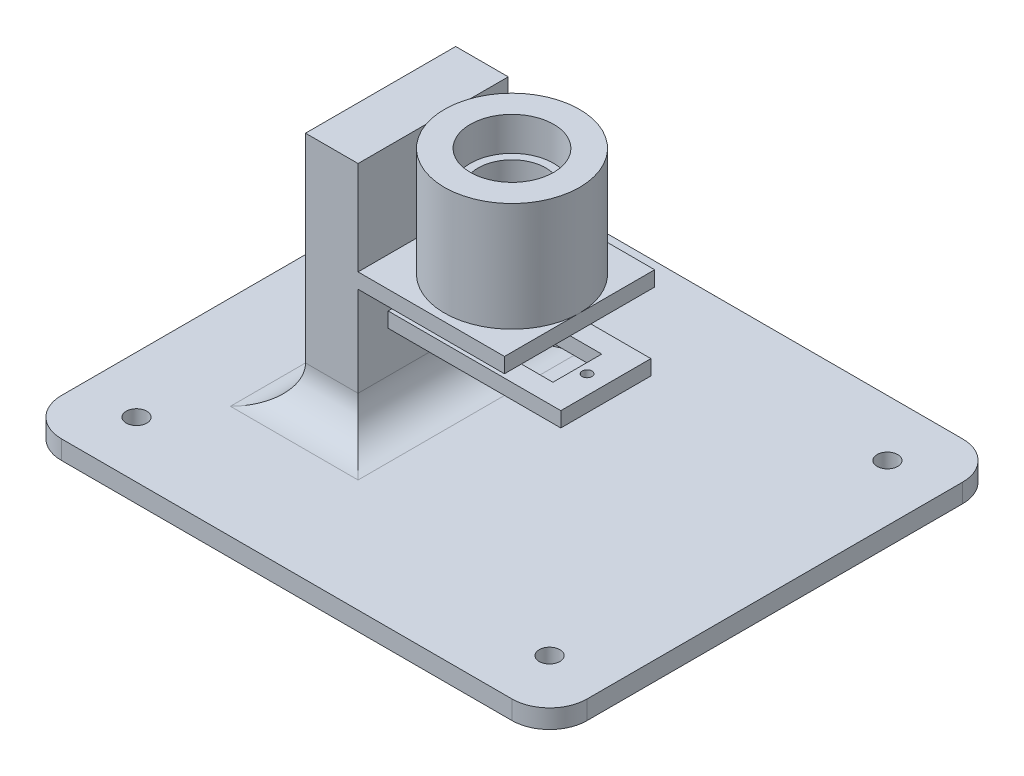
SolidWorks part; units mm, degrees
ref_plane "Front Plane" through (0, 0, 0) normal (0, 0, 1) x (1, 0, 0)
ref_plane "Top Plane" through (0, 0, 0) normal (0, 1, 0) x (1, 0, 0)
ref_plane "Right Plane" through (0, 0, 0) normal (1, 0, 0) x (0, 0, -1)
sketch "Bench_footprint_140x120_profile" plane through (0, 0, 0) normal (0, 1, 0) x (1, 0, 0)
  line L1 (-60, -60) -> (60, -60)
  line L2 (-70, -50) -> (-70, 50)
  line L3 (-60, 60) -> (60, 60)
  line L4 (70, -50) -> (70, 50)
  arc A1 (-60, -60) -> (-70, -50) centre (-60, -50) cw
  arc A2 (60, -60) -> (70, -50) centre (60, -50) ccw
  arc A3 (60, 60) -> (70, 50) centre (60, 50) cw
  arc A4 (-70, 50) -> (-60, 60) centre (-60, 50) cw
  point P4 (-70, -60)
  point P10 (70, -60)
  point P15 (-70, 60)
  dimension "D5" = 10
  dimension "D1" = 140
  dimension "D2" = 120
  dimension "D3" = 60
  dimension "D4" = 70
extrude "Bench_footprint_140x120" add sketch "Bench_footprint_140x120_profile" along normal blind 5
sketch "Backbone_profile" plane through (0, 0, 0) normal (0, 0, 1) x (1, 0, 0)
  line L0 (-60, 5) -> (60, 5) construction
  line L1 (-35, 5) -> (-21, 5)
  line L2 (-35, 5) -> (-35, 68)
  line L3 (-35, 68) -> (-21, 68)
  line L4 (-21, 5) -> (-21, 68)
  dimension "D1" = 14
  dimension "D2" = 63
  dimension "D3" = 35
  dimension "D4" = 0
extrude "Backbone" add sketch "Backbone_profile" along normal blind 40 from offset 20
sketch "Servo_shelf_profile" plane through (0, 0, 0) normal (0, 1, 0) x (1, 0, 0)
  line L1 (-35, -12) -> (25, -12)
  line L2 (-35, -12) -> (-35, 12)
  line L3 (-35, 12) -> (25, 12)
  line L4 (25, -12) -> (25, 12)
  dimension "D1" = 60
  dimension "D2" = 24
extrude "Servo_shelf" add sketch "Servo_shelf_profile" along normal blind 4 from offset 26
sketch "Servo_body_window_profile" plane through (0, 0, 0) normal (0, 1, 0) x (1, 0, 0)
  line L1 (-6.4, -6.5) -> (17.4, -6.5)
  line L2 (-6.4, -6.5) -> (-6.4, 6.5)
  line L3 (-6.4, 6.5) -> (17.4, 6.5)
  line L4 (17.4, -6.5) -> (17.4, 6.5)
  dimension "D1" = 23.8
  dimension "D2" = 13
extrude "Servo_body_window" cut sketch "Servo_body_window_profile" along normal through all from offset 25
sketch "Yaw_servo_fasteners_profile" plane through (0, 0, 0) normal (0, 1, 0) x (1, 0, 0)
  circle A0 centre (-9, 0) radius 1.3
  circle A1 centre (20, 0) radius 1.3
  dimension "D1" = 2.6
  dimension "D2" = 2.6
extrude "Yaw_servo_fasteners" cut sketch "Yaw_servo_fasteners_profile" along normal through all from offset 25
sketch "Bearing_bridge_profile" plane through (0, 0, 0) normal (0, 1, 0) x (1, 0, 0)
  line L1 (-35, -20) -> (18, -20)
  line L2 (-35, -20) -> (-35, 20)
  line L3 (-35, 20) -> (18, 20)
  line L4 (18, -20) -> (18, 20)
  dimension "D1" = 53
  dimension "D2" = 40
extrude "Bearing_bridge" add sketch "Bearing_bridge_profile" along normal blind 4 from offset 39
sketch "Bridge_horn_clearance_profile" plane through (0, 0, 0) normal (0, 1, 0) x (1, 0, 0)
  circle A0 centre (0, 0) radius 14
  dimension "D1" = 28
extrude "Bridge_horn_clearance" cut sketch "Bridge_horn_clearance_profile" along normal through all from offset 38
sketch "Drive_collar_chamber_profile" plane through (0, 0, 0) normal (0, 1, 0) x (1, 0, 0)
  circle A0 centre (0, 0) radius 18
  circle A1 centre (0, 0) radius 14
  dimension "D1" = 36
  dimension "D2" = 28
extrude "Drive_collar_chamber" add sketch "Drive_collar_chamber_profile" along normal blind 5 from offset 43
sketch "Bearing_tower_profile" plane through (0, 0, 0) normal (0, 1, 0) x (1, 0, 0)
  circle A0 centre (0, 0) radius 18
  circle A1 centre (0, 0) radius 11.1
  dimension "D1" = 36
  dimension "D2" = 22.2
extrude "Bearing_tower" add sketch "Bearing_tower_profile" along normal blind 24 from offset 48
sketch "Bearing_separation_shoulder_profile" plane through (0, 0, 0) normal (0, 1, 0) x (1, 0, 0)
  circle A0 centre (0, 0) radius 11.1
  circle A1 centre (0, 0) radius 9
  dimension "D1" = 22.2
  dimension "D2" = 18
extrude "Bearing_separation_shoulder" add sketch "Bearing_separation_shoulder_profile" along normal blind 8 from offset 55
sketch "Bench_clamp_holes_profile" plane through (0, 0, 0) normal (0, 1, 0) x (1, 0, 0)
  circle A0 centre (-55, -45) radius 2.75
  circle A1 centre (55, -45) radius 2.75
  circle A2 centre (-55, 45) radius 2.75
  circle A3 centre (55, 45) radius 2.75
  dimension "D1" = 5.5
  dimension "D2" = 5.5
  dimension "D3" = 5.5
  dimension "D4" = 5.5
extrude "Bench_clamp_holes" cut sketch "Bench_clamp_holes_profile" along normal through all from offset 1
fillet "Fillet1" radius 10 4 edges at (-35, 5, 0) (-21, 5, 0) (-28, 5, -20) (-28, 5, 20)
